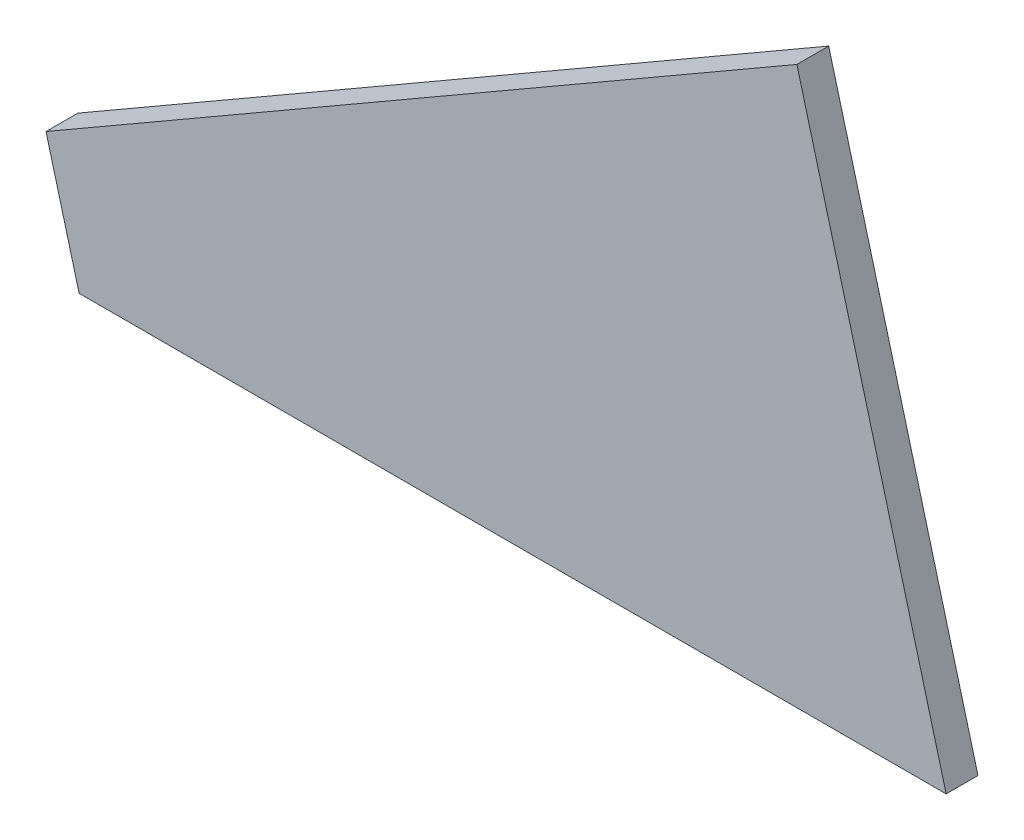
SolidWorks part; units mm, degrees
ref_plane "Front Plane" through (0, 0, 0) normal (0, 0, 1) x (1, 0, 0)
ref_plane "Top Plane" through (0, 0, 0) normal (0, 1, 0) x (1, 0, 0)
ref_plane "Right Plane" through (0, 0, 0) normal (1, 0, 0) x (0, 0, -1)
sketch "Sketch2" plane through (0, 0, 0) normal (0, 0, 1) x (1, 0, 0)
  line L0 (13.4494, 7.765) -> (60.6218, 35)
  line L1 (15.53, 0) -> (13.4494, 7.765)
  line L2 (13.4494, 7.765) -> (7.765, 13.4494)
  line L3 (7.765, 13.4494) -> (0, 15.53)
  line L4 (0, 15.53) -> (-7.765, 13.4494)
  line L5 (-7.765, 13.4494) -> (-13.4494, 7.765)
  line L6 (-13.4494, 7.765) -> (-15.53, 0)
  line L7 (-15.53, 0) -> (-13.4494, -7.765)
  line L8 (-13.4494, -7.765) -> (-7.765, -13.4494)
  line L9 (-7.765, -13.4494) -> (0, -15.53)
  line L10 (0, -15.53) -> (7.765, -13.4494)
  line L11 (7.765, -13.4494) -> (13.4494, -7.765)
  line L12 (13.4494, -7.765) -> (15.53, 0)
  line L13 (70, 0) -> (60.6218, 35)
  line L14 (60.6218, 35) -> (35, 60.6218)
  line L15 (35, 60.6218) -> (0, 70)
  line L16 (0, 70) -> (-35, 60.6218)
  line L17 (-35, 60.6218) -> (-60.6218, 35)
  line L18 (-60.6218, 35) -> (-70, 0)
  line L19 (-70, 0) -> (-60.6218, -35)
  line L20 (-60.6218, -35) -> (-35, -60.6218)
  line L21 (-35, -60.6218) -> (0, -70)
  line L22 (0, -70) -> (35, -60.6218)
  line L23 (35, -60.6218) -> (60.6218, -35)
  line L24 (60.6218, -35) -> (70, 0)
  line L25 (15.53, 0) -> (70, 0)
  circle A0 centre (0, 0) radius 15.0008 construction
  circle A1 centre (0, 0) radius 67.6148 construction
extrude "Boss-Extrude1" add sketch "Sketch2" along normal blind 2 contours L1 L25 L13 L0
